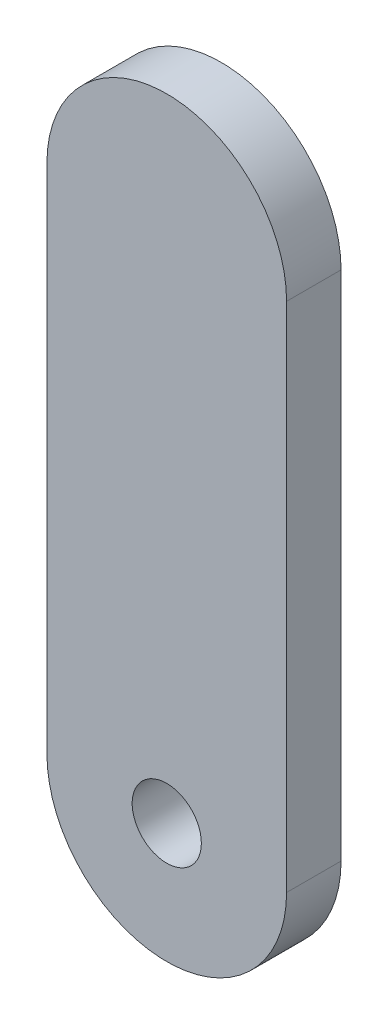
SolidWorks part; units mm, degrees
material "Plain Carbon Steel"
ref_plane "Front Plane" through (0, 0, 0) normal (0, 0, 1) x (1, 0, 0)
ref_plane "Top Plane" through (0, 0, 0) normal (0, 1, 0) x (1, 0, 0)
ref_plane "Right Plane" through (0, 0, 0) normal (1, 0, 0) x (0, 0, -1)
sketch "Sketch1" plane through (0, 0, 0) normal (0, 0, 1) x (1, 0, 0)
  line L0 (11, 0) -> (11, 47)
  line L1 (-11, 47) -> (-11, 0)
  arc A0 (-11, 0) -> (11, 0) centre (0, 0) ccw
  arc A1 (11, 47) -> (-11, 47) centre (0, 47) ccw
  circle A2 centre (0, 0) radius 3.175
  dimension "D1" = 6.35
extrude "Boss-Extrude1" add sketch "Sketch1" along normal blind 5
